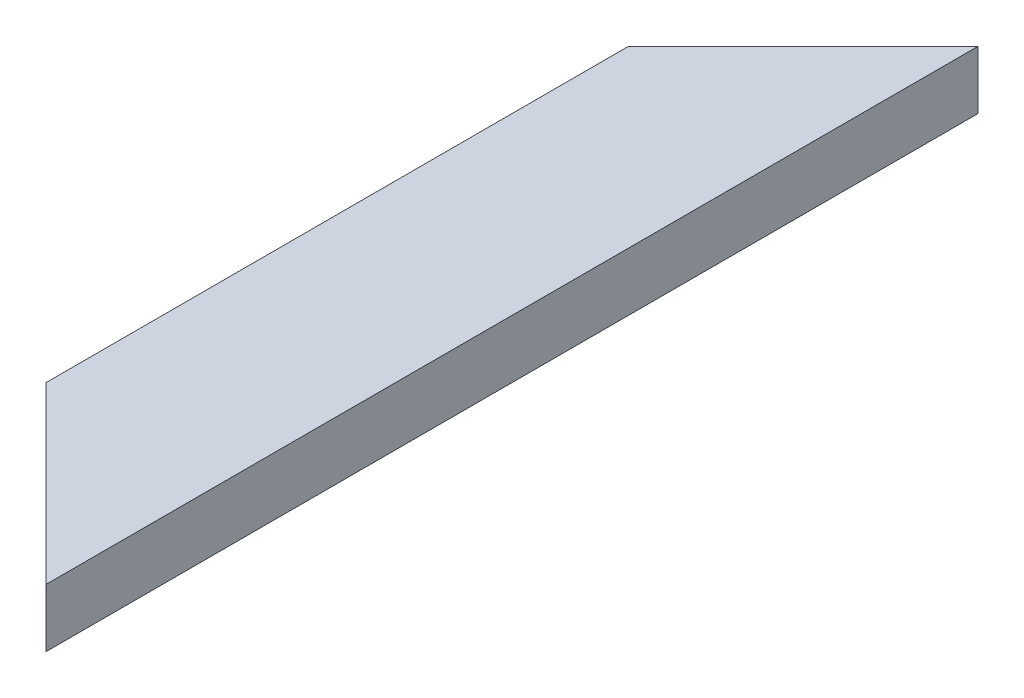
SolidWorks part; units mm, degrees
ref_plane "Front Plane" through (0, 0, 0) normal (0, 0, 1) x (1, 0, 0)
ref_plane "Top Plane" through (0, 0, 0) normal (0, 1, 0) x (1, 0, 0)
ref_plane "Right Plane" through (0, 0, 0) normal (1, 0, 0) x (0, 0, -1)
sketch "Sketch1" plane through (0, 0, 0) normal (0, 0, 1) x (1, 0, 0)
  line L1 (0, 0) -> (152.4, 0)
  line L2 (0, 0) -> (0, -50.8)
  line L3 (0, -50.8) -> (152.4, -50.8)
  line L4 (152.4, 0) -> (152.4, -50.8)
  dimension "D1" = 50.8
  dimension "D2" = 152.4
extrude "Boss-Extrude1" add sketch "Sketch1" along normal blind 812.8
sketch "Sketch2" plane through (0, 0, 0) normal (0, 1, 0) x (1, 0, 0)
  line L0 (152.4, 0) -> (0, -152.4)
  line L1 (0, -812.8) -> (0, 0) construction
  line L2 (152.4, -812.8) -> (0, -660.4)
  line L3 (152.4, -812.8) -> (0, -812.8) construction
  line L4 (152.4, 0) -> (0, 0) construction
  line L5 (0, -660.4) -> (0, -812.8)
  line L6 (0, -812.8) -> (152.4, -812.8)
  line L7 (0, -152.4) -> (0, 0)
  line L8 (0, 0) -> (152.4, 0)
  dimension "D1" = 45
  dimension "D2" = 45
extrude "Cut-Extrude1" cut sketch "Sketch2" against normal blind 711.2
